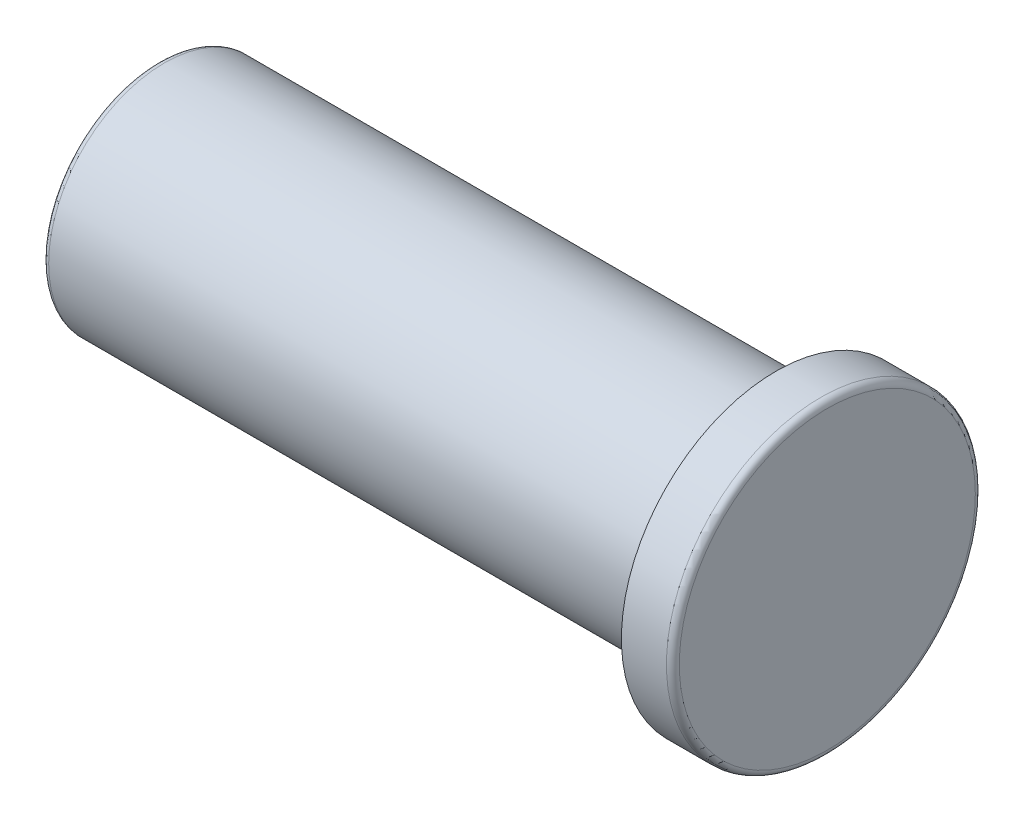
SolidWorks part; units mm, degrees
other "标注1"
sketch "草图3" plane through (-48, -12, -12) normal (-0.2079, -0.8481, -0.4874) x (0.9656, -0.0986, -0.2405)
ref_plane "前视基准面" through (0, 0, 0) normal (0, 0, 1) x (1, 0, 0)
ref_plane "上视基准面" through (0, 0, 0) normal (0, 1, 0) x (1, 0, 0)
ref_plane "右视基准面" through (0, 0, 0) normal (1, 0, 0) x (0, 0, -1)
other "Configuration Table"
sketch "草图1" plane through (0, 0, 0) normal (1, 0, 0) x (0, 0, -1)
  circle A0 centre (0, 0) radius 9
  dimension "D1" = 18
extrude "凸台-拉伸1" add sketch "草图1" against normal blind 48
sketch "草图2" plane through (0, 0, 0) normal (1, 0, 0) x (0, 0, -1)
  circle A0 centre (0, 0) radius 12
  dimension "D1" = 24
extrude "凸台-拉伸2" add sketch "草图2" along normal blind 4
fillet "圆角1" radius 0.5 1 edges at (4, 0, -12)
fillet "圆角2" radius 0.5 1 edges at (-48, 0, -9)
